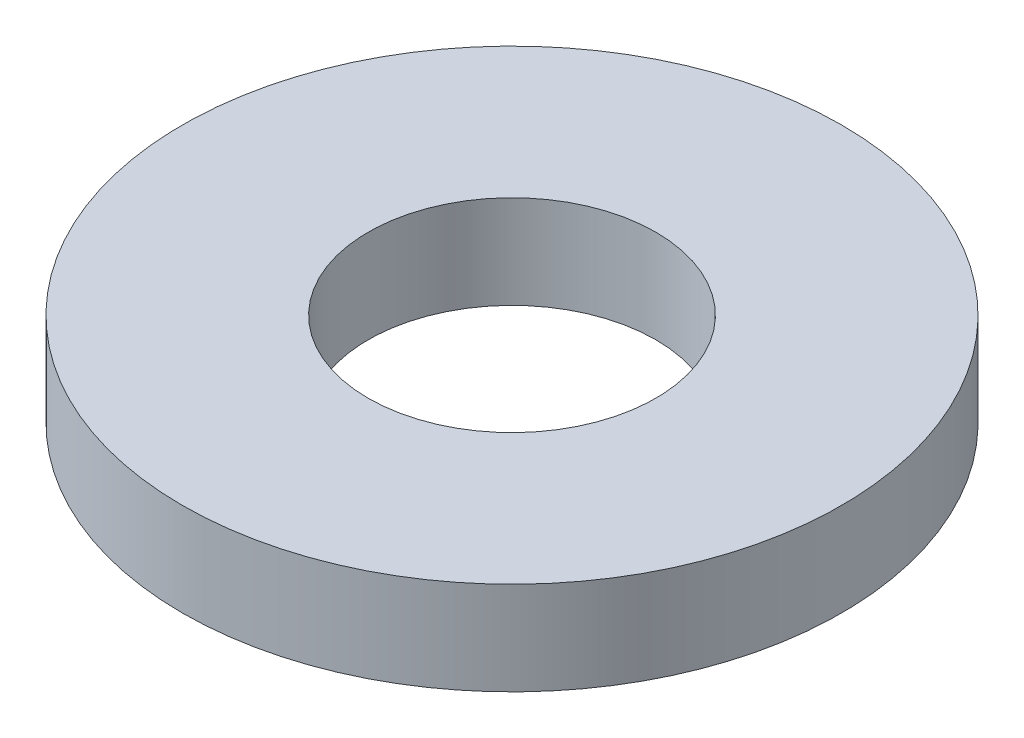
SolidWorks part; units mm, degrees
ref_plane "Front" through (0, 0, 0) normal (0, 0, 1) x (1, 0, 0)
ref_plane "Top" through (0, 0, 0) normal (0, 1, 0) x (1, 0, 0)
ref_plane "Right" through (0, 0, 0) normal (1, 0, 0) x (0, 0, -1)
sketch "Sketch1" plane through (0, 0, 0) normal (0, 1, 0) x (1, 0, 0)
  circle A0 centre (0, 0) radius 1.975
  circle A1 centre (0, 0) radius 4.525
  dimension "D1" = 3.95
  dimension "D2" = 9.05
extrude "Boss-Extrude1" add sketch "Sketch1" along normal blind 1.28
